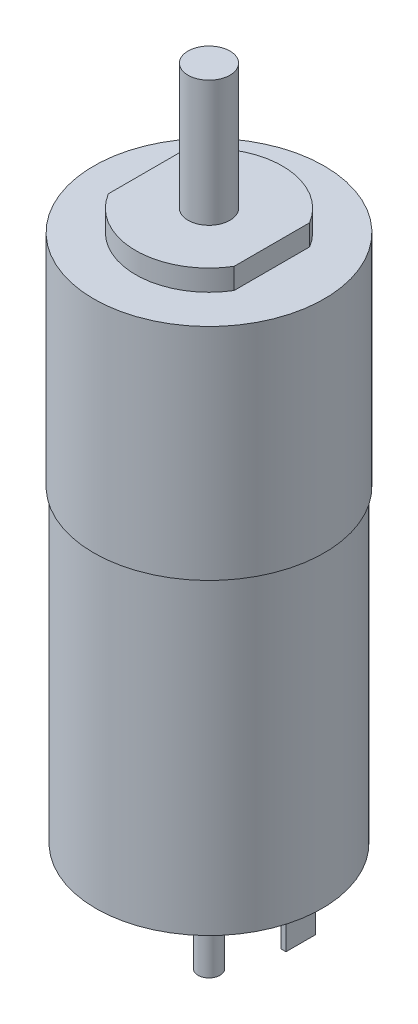
SolidWorks part; units mm, degrees
material "201 Annealed Stainless Steel (SS)"
ref_plane "Front Plane" through (0, 0, 0) normal (0, 0, 1) x (1, 0, 0)
ref_plane "Top Plane" through (0, 0, 0) normal (0, 1, 0) x (1, 0, 0)
ref_plane "Right Plane" through (0, 0, 0) normal (1, 0, 0) x (0, 0, -1)
sketch "Sketch2" plane through (0, 0, 0) normal (0, 1, 0) x (1, 0, 0)
  circle A0 centre (0, 0) radius 10.8
  dimension "D1" = 21.6
extrude "Boss-Extrude1" add sketch "Sketch2" along normal blind 29.5
sketch "Sketch3" plane through (0, 29.5, 0) normal (0, 1, 0) x (1, 0, 0)
  circle A0 centre (0, 0) radius 11
  dimension "D1" = 22
extrude "Boss-Extrude2" add sketch "Sketch3" along normal blind 21
sketch "Sketch4" plane through (0, 50.5, 0) normal (0, 1, 0) x (1, 0, 0)
  line L0 (-6, 0) -> (6, 0) construction
  line L1 (6, 3.6056) -> (6, -3.6056)
  line L2 (-6, 3.6056) -> (-6, -3.6056)
  arc A0 (-6, -3.6056) -> (6, -3.6056) centre (0, 0) ccw
  arc A1 (6, 3.6056) -> (-6, 3.6056) centre (0, 0) ccw
  dimension "D1" = 14
  dimension "D2" = 12
extrude "Boss-Extrude3" add sketch "Sketch4" along normal blind 2
sketch "Sketch5" plane through (0, 52.5, 0) normal (0, 1, 0) x (1, 0, 0)
  circle A0 centre (0, 0) radius 2
  dimension "D1" = 4
extrude "Boss-Extrude4" add sketch "Sketch5" along normal blind 12
sketch "Sketch6" plane through (0, 0, 0) normal (0, -1, 0) x (1, 0, 0)
  circle A0 centre (0, 0) radius 3.75
  dimension "D1" = 7.5
extrude "Boss-Extrude5" add sketch "Sketch6" along normal blind 2
sketch "Sketch7" plane through (0, 0, 0) normal (0, -1, 0) x (1, 0, 0)
  line L0 (-8.25, 0) -> (8.25, 0) construction
  line L1 (-8.75, 1.4) -> (-8.25, 1.4)
  line L2 (-8.75, 1.4) -> (-8.75, -1.4)
  line L3 (-8.75, -1.4) -> (-8.25, -1.4)
  line L4 (-8.25, 1.4) -> (-8.25, -1.4)
  line L5 (8.25, 1.4) -> (8.75, 1.4)
  line L6 (8.25, 1.4) -> (8.25, -1.4)
  line L7 (8.25, -1.4) -> (8.75, -1.4)
  line L8 (8.75, 1.4) -> (8.75, -1.4)
  point P8 (8.75, 0)
  point P12 (0, 0)
  dimension "D1" = 2.8
  dimension "D2" = 0.5
  dimension "D3" = 16.5
extrude "Boss-Extrude6" add sketch "Sketch7" along normal blind 3.9
sketch "Sketch8" plane through (0, -2, 0) normal (0, -1, 0) x (1, 0, 0)
  circle A0 centre (0, 0) radius 1.05
  dimension "D1" = 2.1
extrude "Boss-Extrude7" add sketch "Sketch8" along normal blind 8.4
